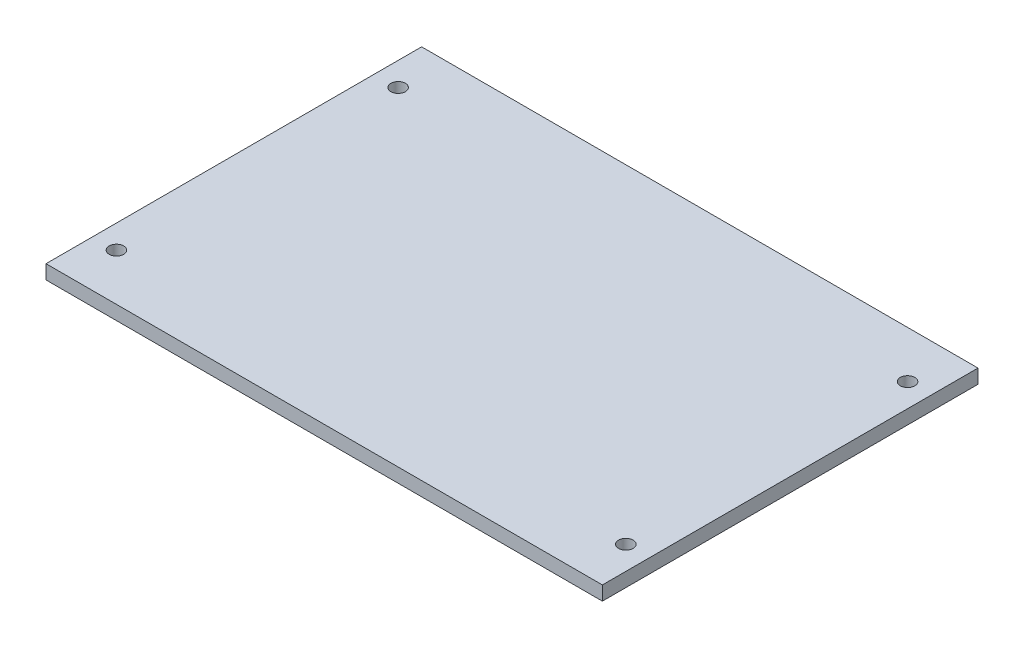
SolidWorks part; units mm, degrees
ref_plane "前视基准面" through (0, 0, 0) normal (0, 0, 1) x (1, 0, 0)
ref_plane "上视基准面" through (0, 0, 0) normal (0, 1, 0) x (1, 0, 0)
ref_plane "右视基准面" through (0, 0, 0) normal (1, 0, 0) x (0, 0, -1)
other "Configuration Table"
sketch "草图1" plane through (0, 0, 0) normal (0, 0, 1) x (1, 0, 0)
  line L10 (0, 0) -> (118.5, 0)
  line L11 (0, 0) -> (0, 3)
  line L12 (0, 3) -> (118.5, 3)
  line L13 (118.5, 0) -> (118.5, 3)
  dimension "D1" = 118.5
  dimension "D2" = 3
extrude "凸台-拉伸1" add sketch "草图1" along normal blind 80
sketch "草图2" plane through (0, 3, 0) normal (0, 1, 0) x (1, 0, 0)
  line L0 (59.25, 0) -> (59.25, -22.575) construction
  line L1 (118.5, 0) -> (0, 0) construction
  line L2 (118.5, -40) -> (147.2193, -40) construction
  line L3 (118.5, -80) -> (118.5, 0) construction
  line L4 (0, -80) -> (0, 0) construction
  circle A0 centre (5, -10) radius 1.55
  circle A1 centre (5, -70) radius 1.55
  circle A2 centre (113.5, -70) radius 1.55
  circle A3 centre (113.5, -10) radius 1.55
  dimension "D3" = 3.1
  dimension "D1" = 5
  dimension "D2" = 30
extrude "切除-拉伸1" cut sketch "草图2" against normal up to next
